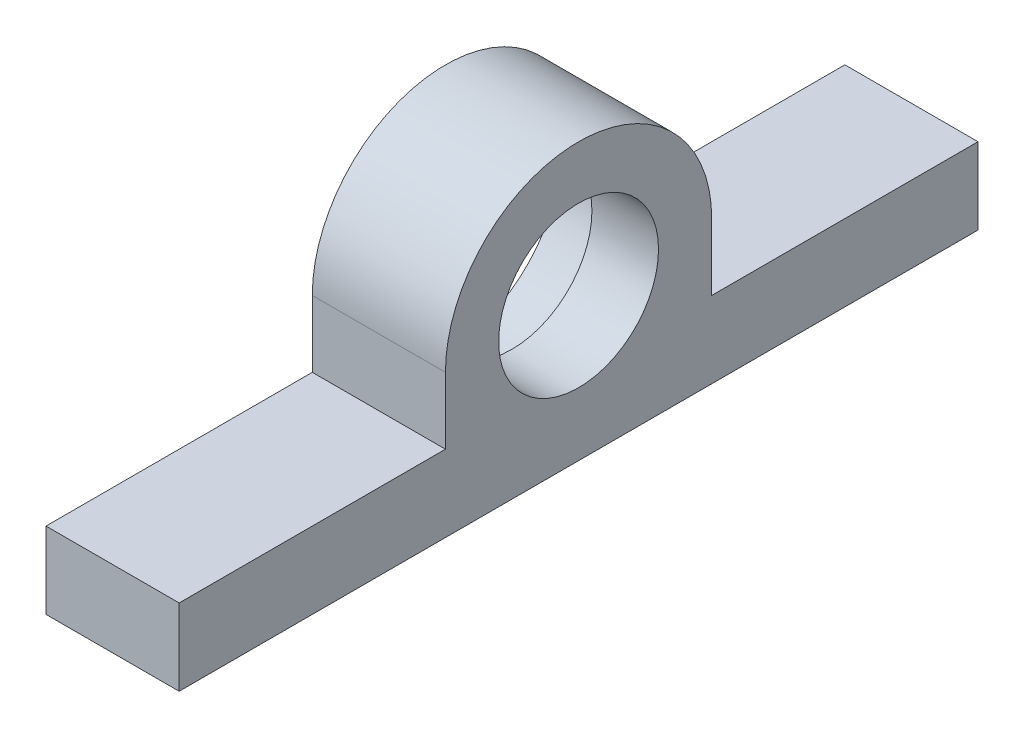
SolidWorks part; units mm, degrees
ref_plane "Front Plane" through (0, 0, 0) normal (0, 0, 1) x (1, 0, 0)
ref_plane "Top Plane" through (0, 0, 0) normal (0, 1, 0) x (1, 0, 0)
ref_plane "Right Plane" through (0, 0, 0) normal (1, 0, 0) x (0, 0, -1)
sketch "Sketch1" plane through (0, 0, 0) normal (1, 0, 0) x (0, 0, -1)
  line L0 (0, 0) -> (76.2, 0)
  line L1 (76.2, 0) -> (76.2, 7.3)
  line L2 (76.2, 7.3) -> (50.8, 7.3)
  line L3 (0, 7.3) -> (0, 0)
  line L5 (50.8, 7.3) -> (50.8, 13.65)
  line L7 (25.4, 13.65) -> (25.4, 7.3)
  line L9 (25.4, 7.3) -> (0, 7.3)
  arc A0 (50.8, 13.65) -> (25.4, 13.65) centre (38.1, 13.65) ccw
  dimension "D1" = 76.2
  dimension "D2" = 7.3
  dimension "D3" = 25.4
  dimension "D4" = 25.4
  dimension "D5" = 6.35
extrude "Boss-Extrude1" add sketch "Sketch1" along normal blind 12.7
sketch "Sketch2" plane through (12.7, 0, 0) normal (1, 0, 0) x (0, 0, -1)
  circle A0 centre (38.1, 13.65) radius 7.625
  dimension "D1" = 15.25
extrude "Cut-Extrude1" cut sketch "Sketch2" against normal through all
sketch "Sketch3" plane through (0, 0, 0) normal (0, -1, 0) x (1, 0, 0)
  line L0 (12.7, -76.2) -> (0, -76.2) construction
  line L3 (12.7, 0) -> (0, 0) construction
  circle A0 centre (6.35, -12.7) radius 2
  circle A1 centre (6.35, -63.5) radius 2
  point P4 (6.35, 0)
  point P10 (6.35, -76.2)
  dimension "D1" = 4
  dimension "D4" = 4
  dimension "D6" = 12.7
  dimension "D2" = 0
  dimension "D3" = 12.7
  dimension "D5" = 0
  dimension "D7" = 50.8
extrude "Cut-Extrude2" cut sketch "Sketch3" against normal blind 7
sketch "Sketch4" plane through (0, 0, 0) normal (-1, 0, 0) x (0, 0, 1)
  circle A0 centre (-38.1, 13.65) radius 11
  dimension "D1" = 22
extrude "Cut-Extrude3" cut sketch "Sketch4" against normal blind 6.35
equation "\"bearing_d\"= 0.5in"
equation "\"heat_set_d\"= 0.1in"
